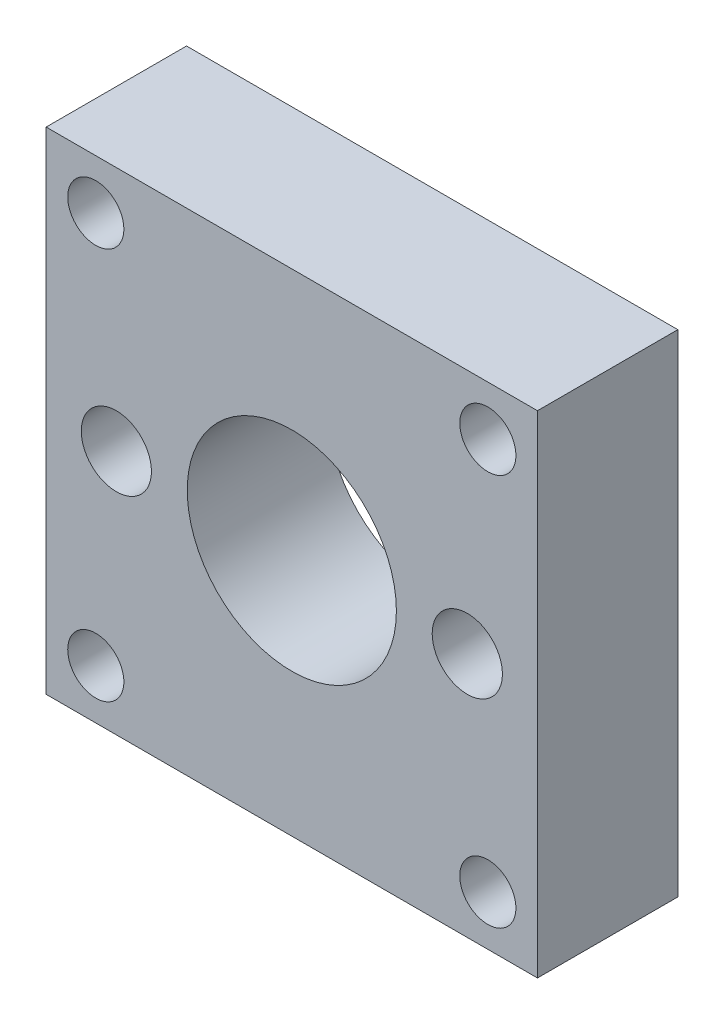
SolidWorks part; units mm, degrees
ref_plane "Front Plane" through (0, 0, 0) normal (0, 0, 1) x (1, 0, 0)
ref_plane "Top Plane" through (0, 0, 0) normal (0, 1, 0) x (1, 0, 0)
ref_plane "Right Plane" through (0, 0, 0) normal (1, 0, 0) x (0, 0, -1)
sketch "Sketch1" plane through (0, 0, 0) normal (0, 0, 1) x (1, 0, 0)
  line L0 (-14.7222, 2.4703) -> (20.2778, 2.4703) construction
  line L1 (-14.7222, 19.9703) -> (20.2778, 19.9703)
  line L2 (-14.7222, 19.9703) -> (-14.7222, -15.0297)
  line L3 (-14.7222, -15.0297) -> (20.2778, -15.0297)
  line L4 (20.2778, 19.9703) -> (20.2778, -15.0297)
  line L5 (-14.7222, 19.9703) -> (20.2778, -15.0297) construction
  line L6 (20.2778, 19.9703) -> (-14.7222, -15.0297) construction
  line L7 (2.7778, 19.9703) -> (2.7778, -15.0297) construction
  circle A0 centre (2.7778, 2.5926) radius 7.45
  circle A1 centre (16.7422, -11.4942) radius 2
  circle A2 centre (16.7422, 16.4347) radius 2
  circle A3 centre (-11.1867, 16.4347) radius 2
  circle A4 centre (-11.1867, -11.4942) radius 2
  circle A5 centre (15.2778, 2.4703) radius 2.5
  circle A6 centre (-9.7222, 2.4703) radius 2.5
  point P4 (2.7778, 2.5926)
  dimension "D3" = 14.9
  dimension "D4" = 4
  dimension "D6" = 5
  dimension "D1" = 35
  dimension "D2" = 35
  dimension "D5" = 5
extrude "Boss-Extrude1" add sketch "Sketch1" along normal blind 10
